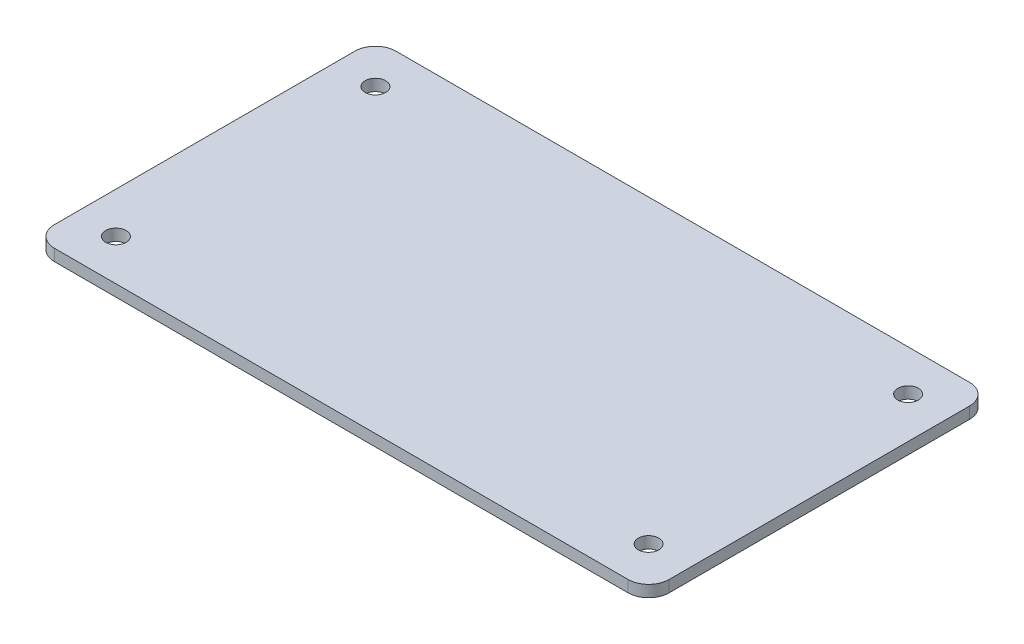
SolidWorks part; units mm, degrees
ref_plane "前视基准面" through (0, 0, 0) normal (0, 0, 1) x (1, 0, 0)
ref_plane "上视基准面" through (0, 0, 0) normal (0, 1, 0) x (1, 0, 0)
ref_plane "右视基准面" through (0, 0, 0) normal (1, 0, 0) x (0, 0, -1)
other "Configuration Table"
sketch "草图1" plane through (0, 0, 0) normal (0, 1, 0) x (1, 0, 0)
  line L1 (-42, -25) -> (42, -25)
  line L2 (-45, -22) -> (-45, 22)
  line L3 (-42, 25) -> (42, 25)
  line L4 (45, -22) -> (45, 22)
  line L5 (-45, -25) -> (45, 25) construction
  line L6 (-45, 25) -> (45, -25) construction
  arc A0 (-42, -25) -> (-45, -22) centre (-42, -22) cw
  arc A1 (45, -22) -> (42, -25) centre (42, -22) cw
  arc A2 (45, 22) -> (42, 25) centre (42, 22) ccw
  arc A3 (-45, 22) -> (-42, 25) centre (-42, 22) cw
  circle A4 centre (-39, 19) radius 1.5
  circle A5 centre (39, 19) radius 1.5
  circle A6 centre (-39, -19) radius 1.5
  circle A7 centre (39, -19) radius 1.5
  point P0 (0, 0)
  dimension "D3" = 3
  dimension "D4" = 3
  dimension "D1" = 90
  dimension "D2" = 50
  dimension "D5" = 6
  dimension "D6" = 6
  dimension "D7" = 6
  dimension "D8" = 6
extrude "凸台-拉伸1" add sketch "草图1" along normal blind 1.7
